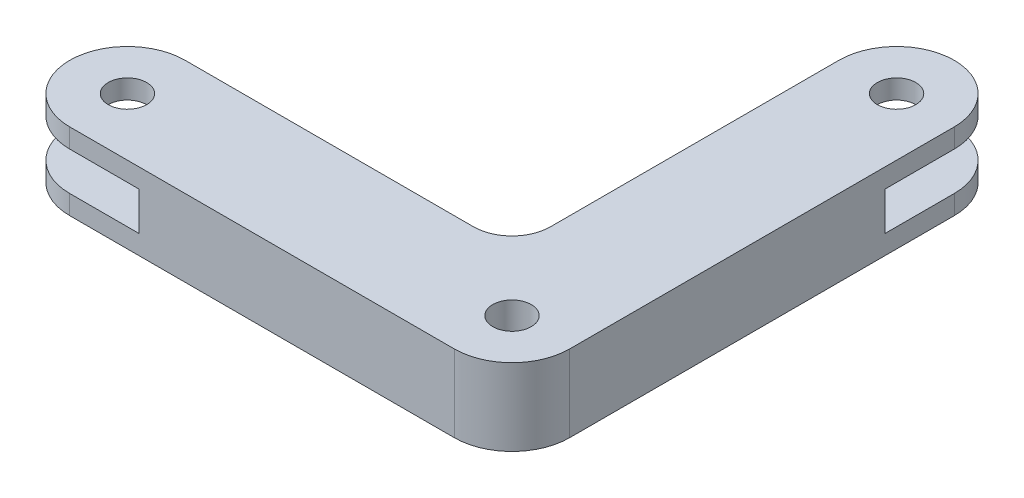
SolidWorks part; units mm, degrees
ref_plane "Front Plane" through (0, 0, 0) normal (0, 0, 1) x (1, 0, 0)
ref_plane "Top Plane" through (0, 0, 0) normal (0, 1, 0) x (1, 0, 0)
ref_plane "Right Plane" through (0, 0, 0) normal (1, 0, 0) x (0, 0, -1)
sketch "Sketch1" plane through (0, 0, 0) normal (0, 1, 0) x (1, 0, 0)
  line L0 (-50, 0) -> (0, 0) construction
  line L3 (-50, 7.5) -> (-12.5, 7.5)
  line L6 (-50, -7.5) -> (0, -7.5)
  line L7 (0, 50) -> (0, 0) construction
  line L8 (7.5, 50) -> (7.5, 0)
  line L9 (-7.5, 50) -> (-7.5, 12.5)
  arc A5 (-50, 7.5) -> (-50, -7.5) centre (-50, 0) ccw
  arc A7 (7.5, 50) -> (-7.5, 50) centre (0, 50) ccw
  arc A8 (0, -7.5) -> (7.5, 0) centre (0, 0) ccw
  arc A9 (-12.5, 7.5) -> (-7.5, 12.5) centre (-12.5, 12.5) ccw
  circle A10 centre (0, 0) radius 2.4
  circle A11 centre (-50, 0) radius 2.4
  circle A12 centre (0, 50) radius 2.4
  point P3 (-25, 0)
  point P10 (0, 25)
  dimension "D1" = 50
  dimension "D5" = 5
  dimension "D2" = 15
  dimension "D3" = 50
  dimension "D4" = 15
extrude "Boss-Extrude1" add sketch "Sketch1" along normal blind 10
ref_plane "Plane1" through (0, 5, 0) normal (0, 1, 0) x (1, 0, 0)
sketch "Sketch2" plane through (0, 5, 0) normal (0, 1, 0) x (1, 0, 0)
  line L0 (-50, -7.5) -> (0, -7.5) construction
  line L1 (-50, 7.5) -> (-41, 7.5)
  line L3 (-50, -7.5) -> (-41, -7.5)
  line L4 (-41, 7.5) -> (-41, -7.5)
  circle A0 centre (-50, 0) radius 2.4
  arc A1 (-50, 7.5) -> (-50, -7.5) centre (-50, 0) ccw
  dimension "D1" = 9
extrude "Cut-Extrude1" cut sketch "Sketch2" against normal blind 2.5 and the other way blind 2.5
sketch "Sketch3" plane through (0, 5, 0) normal (0, 1, 0) x (1, 0, 0)
  line L0 (7.5, 0) -> (7.5, 50) construction
  line L2 (-7.5, 50) -> (-7.5, 41)
  line L3 (-7.5, 41) -> (7.5, 41)
  line L4 (7.5, 50) -> (7.5, 41)
  circle A0 centre (0, 50) radius 2.4
  arc A1 (7.5, 50) -> (-7.5, 50) centre (0, 50) ccw
  dimension "D1" = 9
extrude "Cut-Extrude2" cut sketch "Sketch3" against normal blind 2.5 and the other way blind 2.5
scale "Scale1" scale about centroid uniform scaling yes scale factor 0.8
sketch "Sketch4" plane through (0, 9, 0) normal (0, 1, 0) x (1, 0, 0)
  circle A0 centre (-2.4489, 42.4489) radius 2
  circle A1 centre (-2.4489, 2.4489) radius 2
  circle A2 centre (-42.4489, 2.4489) radius 2
extrude "Cut-Extrude3" cut sketch "Sketch4" against normal through all
